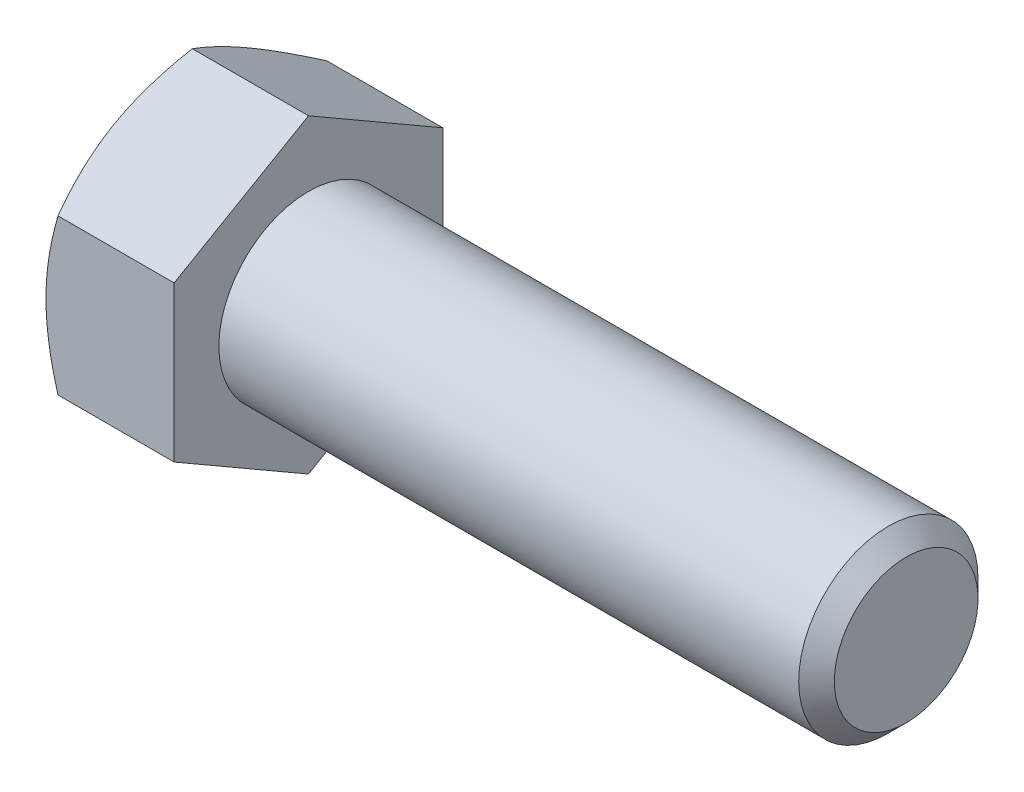
SolidWorks part; units mm, degrees
extrude "BaseHead" add sketch "Sketch1" along normal blind 6.8072
sketch "Sketch1" plane through (0, 0, 0) normal (1, 0, 0) x (0, 0, -1)
  line L0 (7.1374, 4.1208) -> (7.1374, -4.1208)
  line L1 (-7.1374, 4.1208) -> (-7.1374, -4.1208)
  line L2 (7.1374, -4.1208) -> (0, -8.2416)
  line L3 (0, -8.2416) -> (-7.1374, -4.1208)
  line L4 (7.1374, 4.1208) -> (0, 8.2416)
  line L5 (0, 8.2416) -> (-7.1374, 4.1208)
  dimension "D2" = 120
ref_plane "Plane1" through (0, 0, 0) normal (0, 0, 1) x (1, 0, 0)
ref_plane "Plane2" through (0, 0, 0) normal (0, 1, 0) x (1, 0, 0)
ref_plane "Plane3" through (0, 0, 0) normal (1, 0, 0) x (0, 0, -1)
sketch "BodySke" plane through (0, 0, 0) normal (0, 0, 1) x (1, 0, 0)
  line L0 (0, 4.1208) -> (0, -4.1208) construction
  line L1 (0, 0) -> (38.5572, 0)
  line L2 (0, 0) -> (0, 4.7625)
  line L3 (0, 4.7625) -> (37.611, 4.7625)
  line L4 (38.5572, 0) -> (38.5572, 3.8163)
  line L5 (6.8072, 8.2416) -> (6.8072, 4.1208) construction
  line L6 (38.5572, 3.8163) -> (37.611, 4.7625)
  line L7 (0, 0) -> (96.52, 0) construction
  line L8 (38.5572, -3.8163) -> (37.611, -4.7625) construction
  line L9 (0, -4.7625) -> (37.611, -4.7625) construction
  line L10 (8.3947, 15.24) -> (8.3947, -2.54) construction
  line L11 (13.1572, 15.24) -> (13.1572, -2.54) construction
  line L12 (6.8072, 4.1208) -> (6.8072, -4.1208) construction
revolve "BaseBody" add sketch "BodySke" angle 360 about L7
cosmetic thread "ThreadCosmetic" [suppressed] parameters "Thread_length"=25.4, "Thread_minor"=7.6327
sketch "Sketch3" plane through (0, 0, 0) normal (0, 0, 1) x (1, 0, 0)
  line L0 (0, 7.1374) -> (4.3037, 14.5916)
  line L1 (0, 8.2416) -> (0, 4.1208) construction
  line L2 (4.3037, 14.5916) -> (4.3037, 20.9416)
  line L3 (4.3037, 20.9416) -> (-12.7, 20.9416)
  line L4 (-12.7, 20.9416) -> (-12.7, 7.1374)
  line L5 (-12.7, 7.1374) -> (0, 7.1374)
  line L6 (0, 0) -> (99.06, 0) construction
  line L7 (6.8072, 8.2416) -> (0, 8.2416) construction
  dimension "D2" = 6.35
  dimension "D3" = 12.7
  dimension "D4" = 6.35
  dimension "Head_ch_ang" = 30
revolve "HeadChamfer" cut sketch "Sketch3" angle 360 about L6
fillet "HeadFillet" [suppressed] radius 0.762
sketch "ThdSchSke" plane through (0, 0, 0) normal (0, 0, 1) x (1, 0, 0)
  line L0 (13.1572, -3.8163) -> (12.4947, -4.7625)
  line L1 (13.1572, -3.8163) -> (13.8197, -4.7625)
  line L2 (13.8197, -4.7625) -> (13.8197, -5.9531)
  line L3 (-3.175, 0) -> (5.1513, 0) construction
  line L5 (13.8197, -5.9531) -> (12.4947, -5.9531)
  line L6 (12.4947, -5.9531) -> (12.4947, -4.7625)
revolve "ThreadSchematic" [suppressed] cut sketch "ThdSchSke" angle 360 about L3
pattern_linear "ThdSchPat" [suppressed]
equation "\"D3@Sketch1\" = \"Width_flats@Sketch1\" / 2"
equation "\"D4@Sketch1\" = \"D3@Sketch1\""
equation "\"D5@Sketch1\" = \"D4@Sketch1\""
equation "\"Thread_minor@ThreadCosmetic\" = \"Minor_dia@BodySke\""
equation "\"D1@Sketch3\" = \"Width_flats@Sketch1\" / 2"
equation "\"Thread_length@ThreadCosmetic\" = ((sgn( (\"Length@BodySke\" - \"Advance@BodySke\" ) - \"Thread_nom@BodySke\" )-1)*( (\"Length@BodySke\" - \"Advance@BodySke\" ) - \"Thread_nom@BodySke\" ))/-2+ \"Thread_nom@BodySke\""
equation "\"Thread_minor@ThdSchSke\" = \"Minor_dia@BodySke\""
equation "\"Diameter@ThdSchSke\" = \"Diameter@BodySke\""
equation "\"Overcut@ThdSchSke\" = \"Diameter@BodySke\" * 1.25"
equation "\"Start@ThdSchSke\" = \"Head_ht@BaseHead\" + \"Length@BodySke\" - \"Thread_length@ThreadCosmetic\"  '---Non-countersunk---"
equation "\"Num_threads@ThdSchPat\" = int( \"Thread_length@ThreadCosmetic\" / \"Advance@BodySke\" + 0.999 )  + 1"
equation "\"Advance@ThdSchPat\" = \"Thread_length@ThreadCosmetic\" /  (\"Num_threads@ThdSchPat\" - 1) 'relax it"
equation "\"Num_threads@ThdSchPat\" = \"Num_threads@ThdSchPat\" - sgn( \"Num_threads@ThdSchPat\" - 1) '---chamfered tips only---"
